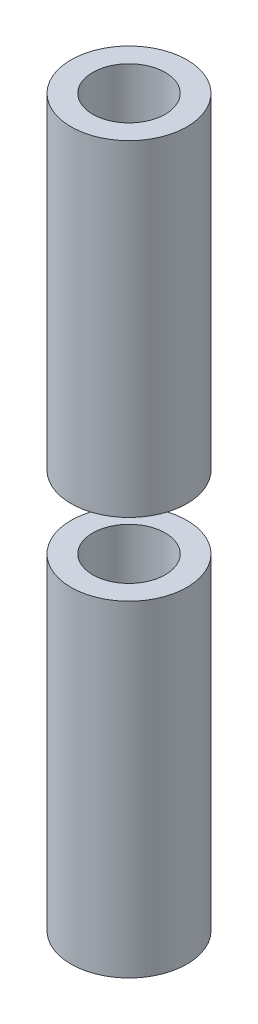
SolidWorks part; units mm, degrees
ref_plane "Front Plane" through (0, 0, 0) normal (0, 0, 1) x (1, 0, 0)
ref_plane "Top Plane" through (0, 0, 0) normal (0, 1, 0) x (1, 0, 0)
ref_plane "Right Plane" through (0, 0, 0) normal (1, 0, 0) x (0, 0, -1)
sketch "Sketch2" plane through (0, 0, 0) normal (0, 1, 0) x (1, 0, 0)
  circle A0 centre (0, 0) radius 2.5
  dimension "D1" = 5
extrude "Boss-Extrude1" add sketch "Sketch2" along normal blind 60
sketch "Sketch4" plane through (0, 0, 0) normal (1, 0, 0) x (0, 0, -1)
  line L0 (-2.5, 60) -> (-2.5, 32.5)
  line L3 (6.2756, 27.5) -> (6.2756, 32.5)
  line L4 (6.2756, 32.5) -> (-9.7296, 32.5)
  line L5 (6.2756, 27.5) -> (-9.7296, 27.5)
  line L6 (-9.7296, 32.5) -> (-9.7296, 27.5)
  line L7 (-2.5, 27.5) -> (-2.5, 0)
extrude "Cut-Extrude1" cut sketch "Sketch4" against normal through all both and the other way through all contours L4 L6 L5 L3
sketch "Sketch5" plane through (0, 32.5, 0) normal (0, -1, 0) x (1, 0, 0)
  circle A0 centre (0, 0) radius 4
  circle A1 centre (0, 0) radius 2.5 construction
  dimension "D1" = 1.5
extrude "Boss-Extrude2" add sketch "Sketch5" against normal through all
sketch "Sketch6" plane through (0, 27.5, 0) normal (0, 1, 0) x (1, 0, 0)
  circle A2 centre (0, 0) radius 4
  circle A3 centre (0, 0) radius 4
  dimension "D1" = 1.5
extrude "Boss-Extrude3" add sketch "Sketch6" against normal through all
sketch "Sketch7" plane through (0, 60, 0) normal (0, 1, 0) x (1, 0, 0)
  circle A0 centre (0, 0) radius 2.5
  dimension "D1" = 5
extrude "Cut-Extrude2" cut sketch "Sketch7" against normal through all both
sketch "Sketch8" plane through (0, 0, 0) normal (1, 0, 0) x (0, 0, -1)
  line L0 (-4, 60) -> (-4, 55)
  line L3 (4, 32.5) -> (4, 60) construction
  line L4 (4, 55) -> (4, 60)
  line L5 (4, 60) -> (-4, 60) construction
  line L6 (4, 60) -> (-4, 60)
  line L7 (-4, 0) -> (4, 0)
  line L8 (4, 0) -> (4, 5)
  line L12 (-4, 5) -> (-4, 0)
  line L13 (4, 55) -> (-4, 55)
  line L14 (-4, 5) -> (4, 5)
extrude "Cut-Extrude3" cut sketch "Sketch8" against normal through all both and the other way through all
